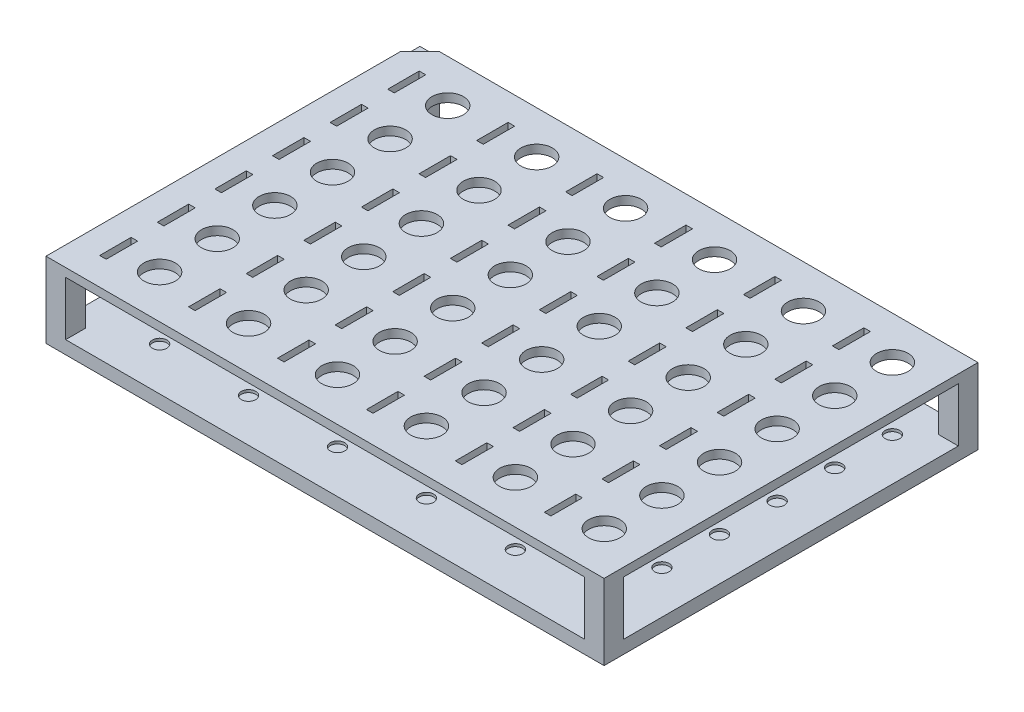
SolidWorks part; units mm, degrees
ref_plane "Front Plane" through (0, 0, 0) normal (0, 0, 1) x (1, 0, 0)
ref_plane "Top Plane" through (0, 0, 0) normal (0, 1, 0) x (1, 0, 0)
ref_plane "Right Plane" through (0, 0, 0) normal (1, 0, 0) x (0, 0, -1)
sketch "Sketch1" plane through (0, 0, 0) normal (0, 1, 0) x (1, 0, 0)
  line L1 (63.88, -42.8) -> (-63.88, -42.8)
  line L2 (63.88, -42.8) -> (63.88, 42.8)
  line L3 (63.88, 42.8) -> (-63.88, 42.8)
  line L4 (-63.88, -42.8) -> (-63.88, 42.8)
  line L5 (63.88, -42.8) -> (-63.88, 42.8) construction
  line L6 (63.88, 42.8) -> (-63.88, -42.8) construction
  point P0 (0, 0)
  dimension "D1" = 127.76
  dimension "D2" = 85.6
extrude "Boss-Extrude1" add sketch "Sketch1" along normal blind 3
ref_plane "Plane1" through (0, 3, 0) normal (0, 1, 0) x (1, 0, 0)
ref_plane "Plane4" through (0, 3, 0) normal (0, 1, 0) x (1, 0, 0)
sketch "Sketch10" plane through (0, 3, 0) normal (0, 1, 0) x (1, 0, 0)
  line L0 (-63.88, 33.02) -> (63.88, 33.02) construction
  line L1 (-63.88, 42.8) -> (-63.88, -42.8) construction
  line L2 (63.88, -42.8) -> (63.88, 42.8) construction
  line L3 (-63.88, -32.925) -> (63.88, -32.925) construction
  line L4 (-47.74, 42.8) -> (-47.74, -42.8) construction
  line L5 (63.88, 42.8) -> (-63.88, 42.8) construction
  line L6 (-63.88, -42.8) -> (63.88, -42.8) construction
  line L7 (54.05, 42.8) -> (54.05, -42.8) construction
  line L8 (-63.88, 19.83) -> (63.88, 19.83) construction
  line L9 (-63.88, 6.64) -> (63.88, 6.64) construction
  line L10 (-63.88, -19.74) -> (63.88, -19.74) construction
  line L11 (-63.88, -6.55) -> (63.88, -6.55) construction
  line L12 (-27.38, 42.8) -> (-27.38, -42.8) construction
  line L13 (-7.02, 42.8) -> (-7.02, -42.8) construction
  line L14 (13.34, 42.8) -> (13.34, -42.8) construction
  line L15 (33.7, 42.8) -> (33.7, -42.8) construction
  circle A0 centre (-47.74, 33.02) radius 1.65
  circle A1 centre (-27.38, 33.02) radius 1.65
  circle A2 centre (-7.02, 33.02) radius 1.65
  circle A3 centre (13.34, 33.02) radius 1.65
  circle A4 centre (33.7, 33.02) radius 1.65
  circle A5 centre (54.06, 33.02) radius 1.65
  circle A6 centre (-47.74, 19.83) radius 1.65
  circle A7 centre (-27.38, 19.83) radius 1.65
  circle A8 centre (-7.02, 19.83) radius 1.65
  circle A9 centre (13.34, 19.83) radius 1.65
  circle A10 centre (33.7, 19.83) radius 1.65
  circle A11 centre (54.06, 19.83) radius 1.65
  circle A12 centre (-47.74, 6.64) radius 1.65
  circle A13 centre (-27.38, 6.64) radius 1.65
  circle A14 centre (-7.02, 6.64) radius 1.65
  circle A15 centre (13.34, 6.64) radius 1.65
  circle A16 centre (33.7, 6.64) radius 1.65
  circle A17 centre (54.06, 6.64) radius 1.65
  circle A18 centre (-47.74, -6.55) radius 1.65
  circle A19 centre (-27.38, -6.55) radius 1.65
  circle A20 centre (-7.02, -6.55) radius 1.65
  circle A21 centre (13.34, -6.55) radius 1.65
  circle A22 centre (33.7, -6.55) radius 1.65
  circle A23 centre (54.06, -6.55) radius 1.65
  circle A24 centre (-47.74, -19.74) radius 1.65
  circle A25 centre (-27.38, -19.74) radius 1.65
  circle A26 centre (-7.02, -19.74) radius 1.65
  circle A27 centre (13.34, -19.74) radius 1.65
  circle A28 centre (33.7, -19.74) radius 1.65
  circle A29 centre (54.06, -19.74) radius 1.65
  circle A30 centre (-47.74, -32.93) radius 1.65
  circle A31 centre (-27.38, -32.93) radius 1.65
  circle A32 centre (-7.02, -32.93) radius 1.65
  circle A33 centre (13.34, -32.93) radius 1.65
  circle A34 centre (33.7, -32.93) radius 1.65
  circle A35 centre (54.06, -32.93) radius 1.65
  dimension "D14" = 3.3
  dimension "D1" = 9.78
  dimension "D2" = 9.875
  dimension "D3" = 13.19
  dimension "D4" = 13.19
  dimension "D5" = 13.19
  dimension "D6" = 13.19
  dimension "D7" = 13.185
  dimension "D8" = 16.14
  dimension "D9" = 20.36
  dimension "D10" = 20.36
  dimension "D11" = 20.36
  dimension "D12" = 20.36
  dimension "D13" = 9.83
  dimension "D15" = 6
  dimension "D16" = 6
extrude "Cut-Extrude2" cut sketch "Sketch10" against normal blind 0.6
sketch "Sketch2" plane through (0, 3, 0) normal (0, 1, 0) x (1, 0, 0)
  line L0 (-63.88, 0) -> (63.88, 0) construction
  line L1 (-63.88, 42.8) -> (-59.38, 42.8)
  line L2 (-63.88, 42.8) -> (-63.88, 38.3)
  line L3 (-63.88, 38.3) -> (-59.38, 38.3)
  line L4 (-59.38, 42.8) -> (-59.38, 38.3)
  line L9 (-63.88, 42.8) -> (-63.88, -42.8) construction
  line L10 (63.88, -42.8) -> (63.88, 42.8) construction
  line L11 (0, 42.8) -> (0, -42.8) construction
  line L12 (63.88, 42.8) -> (-63.88, 42.8) construction
  line L13 (-63.88, -42.8) -> (63.88, -42.8) construction
  line L14 (59.38, 42.8) -> (59.38, 38.3)
  line L15 (63.88, 38.3) -> (59.38, 38.3)
  line L16 (63.88, 42.8) -> (63.88, 38.3)
  line L17 (63.88, 42.8) -> (59.38, 42.8)
  line L18 (63.88, -42.8) -> (59.38, -42.8)
  line L19 (63.88, -42.8) -> (63.88, -38.3)
  line L20 (63.88, -38.3) -> (59.38, -38.3)
  line L21 (59.38, -42.8) -> (59.38, -38.3)
  line L22 (-59.38, -42.8) -> (-59.38, -38.3)
  line L23 (-63.88, -38.3) -> (-59.38, -38.3)
  line L24 (-63.88, -42.8) -> (-63.88, -38.3)
  line L25 (-63.88, -42.8) -> (-59.38, -42.8)
  dimension "D1" = 4.5
extrude "Boss-Extrude2" add sketch "Sketch2" along normal blind 14.3
ref_plane "Plane2" through (0, 17.3, 0) normal (0, 1, 0) x (1, 0, 0)
sketch "Sketch6" plane through (0, 17.3, 0) normal (0, 1, 0) x (1, 0, 0)
  line L1 (-63.88, 42.8) -> (63.88, 42.8)
  line L2 (-63.88, 42.8) -> (-63.88, -42.8)
  line L3 (-63.88, -42.8) -> (63.88, -42.8)
  line L4 (63.88, 42.8) -> (63.88, -42.8)
extrude "Boss-Extrude4" add sketch "Sketch6" against normal blind 1.95
sketch "Sketch7" plane through (0, 17.3, 0) normal (0, 1, 0) x (1, 0, 0)
  line L0 (-57.88, 42.8) -> (-57.88, -42.8) construction
  line L1 (63.88, 42.8) -> (-63.88, 42.8) construction
  line L2 (-63.88, -42.8) -> (63.88, -42.8) construction
  line L3 (57.88, 42.8) -> (57.88, -42.8) construction
  line L4 (-63.88, 36.85) -> (63.88, 36.85) construction
  line L5 (-63.88, 42.8) -> (-63.88, -42.8) construction
  line L6 (63.88, -42.8) -> (63.88, 42.8) construction
  line L7 (-63.88, -36.85) -> (63.88, -36.85) construction
  line L8 (-63.88, 33.025) -> (63.88, 33.025) construction
  line L13 (-63.88, -33.025) -> (63.88, -33.025) construction
  line L14 (54.055, 42.8) -> (54.055, -42.8) construction
  line L15 (57.88, 0) -> (-63.88, 0) construction
  line L21 (25.065, 29.425) -> (23.565, 29.425)
  line L22 (45.425, 29.425) -> (43.925, 29.425)
  line L32 (45.425, 29.425) -> (45.425, 36.625)
  line L33 (45.425, 36.625) -> (43.925, 36.625)
  line L38 (43.925, 29.425) -> (43.925, 36.625)
  line L39 (45.425, 29.425) -> (43.925, 36.625) construction
  line L44 (45.425, 36.625) -> (43.925, 29.425) construction
  line L45 (25.065, 29.425) -> (25.065, 36.625)
  line L46 (25.065, 36.625) -> (23.565, 36.625)
  line L47 (23.565, 29.425) -> (23.565, 36.625)
  line L48 (37.52, 42.8) -> (37.52, -42.8) construction
  line L49 (-84.24, 36.85) -> (43.52, 36.85) construction
  line L50 (-84.24, 33.025) -> (43.52, 33.025) construction
  line L51 (33.695, 42.8) -> (33.695, -42.8) construction
  line L52 (25.065, 29.425) -> (23.565, 36.625) construction
  line L53 (25.065, 36.625) -> (23.565, 29.425) construction
  line L54 (4.705, 29.425) -> (3.205, 29.425)
  line L55 (4.705, 29.425) -> (4.705, 36.625)
  line L56 (4.705, 36.625) -> (3.205, 36.625)
  line L57 (3.205, 29.425) -> (3.205, 36.625)
  line L58 (17.16, 42.8) -> (17.16, -42.8) construction
  line L59 (-104.6, 36.85) -> (23.16, 36.85) construction
  line L60 (-104.6, 33.025) -> (23.16, 33.025) construction
  line L61 (13.335, 42.8) -> (13.335, -42.8) construction
  line L62 (4.705, 29.425) -> (3.205, 36.625) construction
  line L63 (4.705, 36.625) -> (3.205, 29.425) construction
  line L64 (-15.655, 29.425) -> (-17.155, 29.425)
  line L65 (-15.655, 29.425) -> (-15.655, 36.625)
  line L66 (-15.655, 36.625) -> (-17.155, 36.625)
  line L67 (-17.155, 29.425) -> (-17.155, 36.625)
  line L68 (-3.2, 42.8) -> (-3.2, -42.8) construction
  line L69 (-124.96, 36.85) -> (2.8, 36.85) construction
  line L70 (-124.96, 33.025) -> (2.8, 33.025) construction
  line L71 (-7.025, 42.8) -> (-7.025, -42.8) construction
  line L72 (-15.655, 29.425) -> (-17.155, 36.625) construction
  line L73 (-15.655, 36.625) -> (-17.155, 29.425) construction
  line L74 (-36.015, 29.425) -> (-37.515, 29.425)
  line L75 (-36.015, 29.425) -> (-36.015, 36.625)
  line L76 (-36.015, 36.625) -> (-37.515, 36.625)
  line L77 (-37.515, 29.425) -> (-37.515, 36.625)
  line L78 (-23.56, 42.8) -> (-23.56, -42.8) construction
  line L79 (-145.32, 36.85) -> (-17.56, 36.85) construction
  line L80 (-145.32, 33.025) -> (-17.56, 33.025) construction
  line L81 (-27.385, 42.8) -> (-27.385, -42.8) construction
  line L82 (-36.015, 29.425) -> (-37.515, 36.625) construction
  line L83 (-36.015, 36.625) -> (-37.515, 29.425) construction
  line L84 (-56.375, 29.425) -> (-57.875, 29.425)
  line L85 (-56.375, 29.425) -> (-56.375, 36.625)
  line L86 (-56.375, 36.625) -> (-57.875, 36.625)
  line L87 (-57.875, 29.425) -> (-57.875, 36.625)
  line L88 (-43.92, 42.8) -> (-43.92, -42.8) construction
  line L89 (-165.68, 36.85) -> (-37.92, 36.85) construction
  line L90 (-165.68, 33.025) -> (-37.92, 33.025) construction
  line L91 (-47.745, 42.8) -> (-47.745, -42.8) construction
  line L92 (-56.375, 29.425) -> (-57.875, 36.625) construction
  line L93 (-56.375, 36.625) -> (-57.875, 29.425) construction
  line L94 (25.065, 16.235) -> (23.565, 16.235)
  line L95 (45.425, 16.235) -> (43.925, 16.235)
  line L96 (45.425, 16.235) -> (45.425, 23.435)
  line L97 (45.425, 23.435) -> (43.925, 23.435)
  line L98 (43.925, 16.235) -> (43.925, 23.435)
  line L99 (25.065, 16.235) -> (25.065, 23.435)
  line L100 (25.065, 23.435) -> (23.565, 23.435)
  line L101 (23.565, 16.235) -> (23.565, 23.435)
  line L102 (4.705, 16.235) -> (3.205, 16.235)
  line L103 (4.705, 16.235) -> (4.705, 23.435)
  line L104 (4.705, 23.435) -> (3.205, 23.435)
  line L105 (3.205, 16.235) -> (3.205, 23.435)
  line L106 (-15.655, 16.235) -> (-17.155, 16.235)
  line L107 (-15.655, 16.235) -> (-15.655, 23.435)
  line L108 (-15.655, 23.435) -> (-17.155, 23.435)
  line L109 (-17.155, 16.235) -> (-17.155, 23.435)
  line L110 (-36.015, 16.235) -> (-37.515, 16.235)
  line L111 (-36.015, 16.235) -> (-36.015, 23.435)
  line L112 (-36.015, 23.435) -> (-37.515, 23.435)
  line L113 (-37.515, 16.235) -> (-37.515, 23.435)
  line L114 (-56.375, 16.235) -> (-57.875, 16.235)
  line L115 (-56.375, 16.235) -> (-56.375, 23.435)
  line L116 (-56.375, 23.435) -> (-57.875, 23.435)
  line L117 (-57.875, 16.235) -> (-57.875, 23.435)
  line L118 (45.425, 16.235) -> (43.925, 23.435) construction
  line L119 (45.425, 23.435) -> (43.925, 16.235) construction
  line L120 (25.065, 16.235) -> (23.565, 23.435) construction
  line L121 (25.065, 23.435) -> (23.565, 16.235) construction
  line L122 (4.705, 16.235) -> (3.205, 23.435) construction
  line L123 (4.705, 23.435) -> (3.205, 16.235) construction
  line L124 (-15.655, 16.235) -> (-17.155, 23.435) construction
  line L125 (-15.655, 23.435) -> (-17.155, 16.235) construction
  line L126 (-36.015, 16.235) -> (-37.515, 23.435) construction
  line L127 (-36.015, 23.435) -> (-37.515, 16.235) construction
  line L128 (-56.375, 16.235) -> (-57.875, 23.435) construction
  line L129 (-56.375, 23.435) -> (-57.875, 16.235) construction
  line L130 (25.065, 3.045) -> (23.565, 3.045)
  line L131 (45.425, 3.045) -> (43.925, 3.045)
  line L132 (45.425, 3.045) -> (45.425, 10.245)
  line L133 (45.425, 10.245) -> (43.925, 10.245)
  line L134 (43.925, 3.045) -> (43.925, 10.245)
  line L135 (25.065, 3.045) -> (25.065, 10.245)
  line L136 (25.065, 10.245) -> (23.565, 10.245)
  line L137 (23.565, 3.045) -> (23.565, 10.245)
  line L138 (4.705, 3.045) -> (3.205, 3.045)
  line L139 (4.705, 3.045) -> (4.705, 10.245)
  line L140 (4.705, 10.245) -> (3.205, 10.245)
  line L141 (3.205, 3.045) -> (3.205, 10.245)
  line L142 (-15.655, 3.045) -> (-17.155, 3.045)
  line L143 (-15.655, 3.045) -> (-15.655, 10.245)
  line L144 (-15.655, 10.245) -> (-17.155, 10.245)
  line L145 (-17.155, 3.045) -> (-17.155, 10.245)
  line L146 (-36.015, 3.045) -> (-37.515, 3.045)
  line L147 (-36.015, 3.045) -> (-36.015, 10.245)
  line L148 (-36.015, 10.245) -> (-37.515, 10.245)
  line L149 (-37.515, 3.045) -> (-37.515, 10.245)
  line L150 (-56.375, 3.045) -> (-57.875, 3.045)
  line L151 (-56.375, 3.045) -> (-56.375, 10.245)
  line L152 (-56.375, 10.245) -> (-57.875, 10.245)
  line L153 (-57.875, 3.045) -> (-57.875, 10.245)
  line L154 (45.425, 3.045) -> (43.925, 10.245) construction
  line L155 (45.425, 10.245) -> (43.925, 3.045) construction
  line L156 (25.065, 3.045) -> (23.565, 10.245) construction
  line L157 (25.065, 10.245) -> (23.565, 3.045) construction
  line L158 (4.705, 3.045) -> (3.205, 10.245) construction
  line L159 (4.705, 10.245) -> (3.205, 3.045) construction
  line L160 (-15.655, 3.045) -> (-17.155, 10.245) construction
  line L161 (-15.655, 10.245) -> (-17.155, 3.045) construction
  line L162 (-36.015, 3.045) -> (-37.515, 10.245) construction
  line L163 (-36.015, 10.245) -> (-37.515, 3.045) construction
  line L164 (-56.375, 3.045) -> (-57.875, 10.245) construction
  line L165 (-56.375, 10.245) -> (-57.875, 3.045) construction
  line L166 (25.065, -10.145) -> (23.565, -10.145)
  line L167 (45.425, -10.145) -> (43.925, -10.145)
  line L168 (45.425, -10.145) -> (45.425, -2.945)
  line L169 (45.425, -2.945) -> (43.925, -2.945)
  line L170 (43.925, -10.145) -> (43.925, -2.945)
  line L171 (25.065, -10.145) -> (25.065, -2.945)
  line L172 (25.065, -2.945) -> (23.565, -2.945)
  line L173 (23.565, -10.145) -> (23.565, -2.945)
  line L174 (4.705, -10.145) -> (3.205, -10.145)
  line L175 (4.705, -10.145) -> (4.705, -2.945)
  line L176 (4.705, -2.945) -> (3.205, -2.945)
  line L177 (3.205, -10.145) -> (3.205, -2.945)
  line L178 (-15.655, -10.145) -> (-17.155, -10.145)
  line L179 (-15.655, -10.145) -> (-15.655, -2.945)
  line L180 (-15.655, -2.945) -> (-17.155, -2.945)
  line L181 (-17.155, -10.145) -> (-17.155, -2.945)
  line L182 (-36.015, -10.145) -> (-37.515, -10.145)
  line L183 (-36.015, -10.145) -> (-36.015, -2.945)
  line L184 (-36.015, -2.945) -> (-37.515, -2.945)
  line L185 (-37.515, -10.145) -> (-37.515, -2.945)
  line L186 (-56.375, -10.145) -> (-57.875, -10.145)
  line L187 (-56.375, -10.145) -> (-56.375, -2.945)
  line L188 (-56.375, -2.945) -> (-57.875, -2.945)
  line L189 (-57.875, -10.145) -> (-57.875, -2.945)
  line L190 (45.425, -10.145) -> (43.925, -2.945) construction
  line L191 (45.425, -2.945) -> (43.925, -10.145) construction
  line L192 (25.065, -10.145) -> (23.565, -2.945) construction
  line L193 (25.065, -2.945) -> (23.565, -10.145) construction
  line L194 (4.705, -10.145) -> (3.205, -2.945) construction
  line L195 (4.705, -2.945) -> (3.205, -10.145) construction
  line L196 (-15.655, -10.145) -> (-17.155, -2.945) construction
  line L197 (-15.655, -2.945) -> (-17.155, -10.145) construction
  line L198 (-36.015, -10.145) -> (-37.515, -2.945) construction
  line L199 (-36.015, -2.945) -> (-37.515, -10.145) construction
  line L200 (-56.375, -10.145) -> (-57.875, -2.945) construction
  line L201 (-56.375, -2.945) -> (-57.875, -10.145) construction
  line L202 (25.065, -23.335) -> (23.565, -23.335)
  line L203 (45.425, -23.335) -> (43.925, -23.335)
  line L204 (45.425, -23.335) -> (45.425, -16.135)
  line L205 (45.425, -16.135) -> (43.925, -16.135)
  line L206 (43.925, -23.335) -> (43.925, -16.135)
  line L207 (25.065, -23.335) -> (25.065, -16.135)
  line L208 (25.065, -16.135) -> (23.565, -16.135)
  line L209 (23.565, -23.335) -> (23.565, -16.135)
  line L210 (4.705, -23.335) -> (3.205, -23.335)
  line L211 (4.705, -23.335) -> (4.705, -16.135)
  line L212 (4.705, -16.135) -> (3.205, -16.135)
  line L213 (3.205, -23.335) -> (3.205, -16.135)
  line L214 (-15.655, -23.335) -> (-17.155, -23.335)
  line L215 (-15.655, -23.335) -> (-15.655, -16.135)
  line L216 (-15.655, -16.135) -> (-17.155, -16.135)
  line L217 (-17.155, -23.335) -> (-17.155, -16.135)
  line L218 (-36.015, -23.335) -> (-37.515, -23.335)
  line L219 (-36.015, -23.335) -> (-36.015, -16.135)
  line L220 (-36.015, -16.135) -> (-37.515, -16.135)
  line L221 (-37.515, -23.335) -> (-37.515, -16.135)
  line L222 (-56.375, -23.335) -> (-57.875, -23.335)
  line L223 (-56.375, -23.335) -> (-56.375, -16.135)
  line L224 (-56.375, -16.135) -> (-57.875, -16.135)
  line L225 (-57.875, -23.335) -> (-57.875, -16.135)
  line L226 (45.425, -23.335) -> (43.925, -16.135) construction
  line L227 (45.425, -16.135) -> (43.925, -23.335) construction
  line L228 (25.065, -23.335) -> (23.565, -16.135) construction
  line L229 (25.065, -16.135) -> (23.565, -23.335) construction
  line L230 (4.705, -23.335) -> (3.205, -16.135) construction
  line L231 (4.705, -16.135) -> (3.205, -23.335) construction
  line L232 (-15.655, -23.335) -> (-17.155, -16.135) construction
  line L233 (-15.655, -16.135) -> (-17.155, -23.335) construction
  line L234 (-36.015, -23.335) -> (-37.515, -16.135) construction
  line L235 (-36.015, -16.135) -> (-37.515, -23.335) construction
  line L236 (-56.375, -23.335) -> (-57.875, -16.135) construction
  line L237 (-56.375, -16.135) -> (-57.875, -23.335) construction
  line L238 (25.065, -36.525) -> (23.565, -36.525)
  line L239 (45.425, -36.525) -> (43.925, -36.525)
  line L240 (45.425, -36.525) -> (45.425, -29.325)
  line L241 (45.425, -29.325) -> (43.925, -29.325)
  line L242 (43.925, -36.525) -> (43.925, -29.325)
  line L243 (25.065, -36.525) -> (25.065, -29.325)
  line L244 (25.065, -29.325) -> (23.565, -29.325)
  line L245 (23.565, -36.525) -> (23.565, -29.325)
  line L246 (4.705, -36.525) -> (3.205, -36.525)
  line L247 (4.705, -36.525) -> (4.705, -29.325)
  line L248 (4.705, -29.325) -> (3.205, -29.325)
  line L249 (3.205, -36.525) -> (3.205, -29.325)
  line L250 (-15.655, -36.525) -> (-17.155, -36.525)
  line L251 (-15.655, -36.525) -> (-15.655, -29.325)
  line L252 (-15.655, -29.325) -> (-17.155, -29.325)
  line L253 (-17.155, -36.525) -> (-17.155, -29.325)
  line L254 (-36.015, -36.525) -> (-37.515, -36.525)
  line L255 (-36.015, -36.525) -> (-36.015, -29.325)
  line L256 (-36.015, -29.325) -> (-37.515, -29.325)
  line L257 (-37.515, -36.525) -> (-37.515, -29.325)
  line L258 (-56.375, -36.525) -> (-57.875, -36.525)
  line L259 (-56.375, -36.525) -> (-56.375, -29.325)
  line L260 (-56.375, -29.325) -> (-57.875, -29.325)
  line L261 (-57.875, -36.525) -> (-57.875, -29.325)
  line L262 (45.425, -36.525) -> (43.925, -29.325) construction
  line L263 (45.425, -29.325) -> (43.925, -36.525) construction
  line L264 (25.065, -36.525) -> (23.565, -29.325) construction
  line L265 (25.065, -29.325) -> (23.565, -36.525) construction
  line L266 (4.705, -36.525) -> (3.205, -29.325) construction
  line L267 (4.705, -29.325) -> (3.205, -36.525) construction
  line L268 (-15.655, -36.525) -> (-17.155, -29.325) construction
  line L269 (-15.655, -29.325) -> (-17.155, -36.525) construction
  line L270 (-36.015, -36.525) -> (-37.515, -29.325) construction
  line L271 (-36.015, -29.325) -> (-37.515, -36.525) construction
  line L272 (-56.375, -36.525) -> (-57.875, -29.325) construction
  line L273 (-56.375, -29.325) -> (-57.875, -36.525) construction
  circle A43 centre (54.055, 33.025) radius 3.6
  circle A45 centre (54.055, 19.835) radius 3.6
  circle A46 centre (54.055, 6.645) radius 3.6
  circle A47 centre (54.055, -6.545) radius 3.6
  circle A48 centre (54.055, -19.735) radius 3.6
  circle A49 centre (54.055, -32.925) radius 3.6
  circle A56 centre (33.695, 33.025) radius 3.6
  circle A57 centre (33.695, 19.835) radius 3.6
  circle A58 centre (33.695, 6.645) radius 3.6
  circle A59 centre (33.695, -6.545) radius 3.6
  circle A60 centre (33.695, -19.735) radius 3.6
  circle A61 centre (33.695, -32.925) radius 3.6
  circle A62 centre (13.335, 33.025) radius 3.6
  circle A63 centre (13.335, 19.835) radius 3.6
  circle A64 centre (13.335, 6.645) radius 3.6
  circle A65 centre (13.335, -6.545) radius 3.6
  circle A66 centre (13.335, -19.735) radius 3.6
  circle A67 centre (13.335, -32.925) radius 3.6
  circle A68 centre (-7.025, 33.025) radius 3.6
  circle A69 centre (-7.025, 19.835) radius 3.6
  circle A70 centre (-7.025, 6.645) radius 3.6
  circle A71 centre (-7.025, -6.545) radius 3.6
  circle A72 centre (-7.025, -19.735) radius 3.6
  circle A73 centre (-7.025, -32.925) radius 3.6
  circle A74 centre (-27.385, 33.025) radius 3.6
  circle A75 centre (-27.385, 19.835) radius 3.6
  circle A76 centre (-27.385, 6.645) radius 3.6
  circle A77 centre (-27.385, -6.545) radius 3.6
  circle A78 centre (-27.385, -19.735) radius 3.6
  circle A79 centre (-27.385, -32.925) radius 3.6
  circle A80 centre (-47.745, 33.025) radius 3.6
  circle A81 centre (-47.745, 19.835) radius 3.6
  circle A82 centre (-47.745, 6.645) radius 3.6
  circle A83 centre (-47.745, -6.545) radius 3.6
  circle A84 centre (-47.745, -19.735) radius 3.6
  circle A85 centre (-47.745, -32.925) radius 3.6
  point P26 (44.675, 33.025)
  point P44 (24.315, 33.025)
  point P59 (3.955, 33.025)
  point P74 (-16.405, 33.025)
  point P89 (-36.765, 33.025)
  point P104 (-57.125, 33.025)
  point P109 (44.675, 19.835)
  point P116 (24.315, 19.835)
  point P123 (3.955, 19.835)
  point P130 (-16.405, 19.835)
  point P137 (-36.765, 19.835)
  point P144 (-57.125, 19.835)
  point P151 (44.675, 6.645)
  point P158 (24.315, 6.645)
  point P165 (3.955, 6.645)
  point P172 (-16.405, 6.645)
  point P179 (-36.765, 6.645)
  point P186 (-57.125, 6.645)
  point P193 (44.675, -6.545)
  point P200 (24.315, -6.545)
  point P207 (3.955, -6.545)
  point P214 (-16.405, -6.545)
  point P221 (-36.765, -6.545)
  point P228 (-57.125, -6.545)
  point P235 (44.675, -19.735)
  point P242 (24.315, -19.735)
  point P249 (3.955, -19.735)
  point P256 (-16.405, -19.735)
  point P263 (-36.765, -19.735)
  point P270 (-57.125, -19.735)
  point P277 (44.675, -32.925)
  point P284 (24.315, -32.925)
  point P291 (3.955, -32.925)
  point P298 (-16.405, -32.925)
  point P305 (-36.765, -32.925)
  point P312 (-57.125, -32.925)
  dimension "D9" = 6
  dimension "D15" = 6
  dimension "D14" = 6
  dimension "7.8" = 7.2
  dimension "D1" = 5.95
  dimension "D2" = 6
  dimension "D3" = 6
  dimension "D4" = 5.95
  dimension "D5" = 3.825
  dimension "D6" = 3.825
  dimension "D7" = 3.825
  dimension "D8" = 66.05
  dimension "D10" = 1.5
  dimension "D11" = 7.2
  dimension "D12" = 8.63
  dimension "D13" = 6
extrude "Cut-Extrude1" cut sketch "Sketch7" against normal blind 3
ref_plane "Plane5" through (0, 17.3, 0) normal (0, 1, 0) x (1, 0, 0)
sketch "Sketch11" plane through (0, 17.3, 0) normal (0, 1, 0) x (1, 0, 0)
  line L0 (-63.88, 42.8) -> (-59.38, 42.8)
  line L1 (63.88, 42.8) -> (-63.88, 42.8) construction
  line L2 (-63.88, 42.8) -> (-63.88, 38.3)
  line L3 (-63.88, 42.8) -> (-63.88, -42.8) construction
  line L4 (-59.38, 42.8) -> (-63.88, 38.3)
extrude "Cut-Extrude3" cut sketch "Sketch11" against normal blind 1.2
ref_plane "Plane7" through (0, 17.3, 0) normal (0, 1, 0) x (1, 0, 0)
